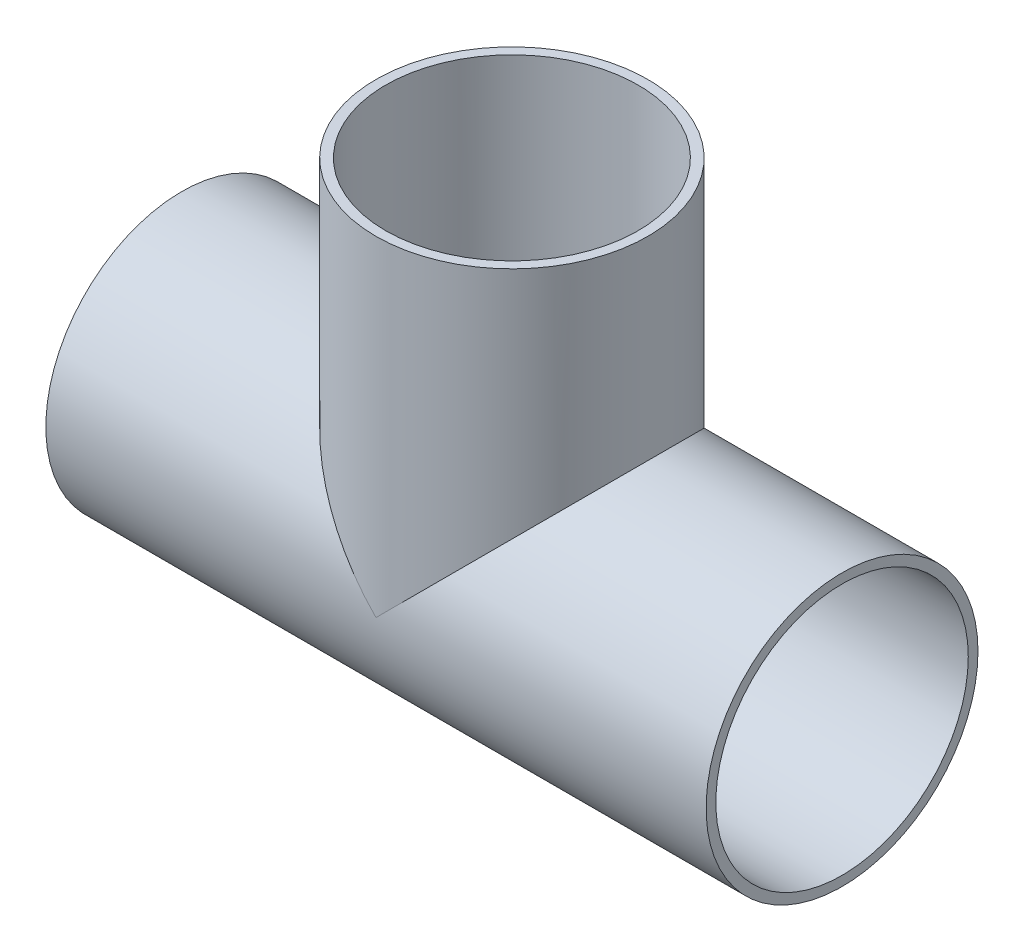
SolidWorks part; units mm, degrees
ref_plane "Front Plane" through (0, 0, 0) normal (0, 0, 1) x (1, 0, 0)
ref_plane "Top Plane" through (0, 0, 0) normal (0, 1, 0) x (1, 0, 0)
ref_plane "Right Plane" through (0, 0, 0) normal (1, 0, 0) x (0, 0, -1)
sketch "Sketch1" plane through (0, 0, 0) normal (1, 0, 0) x (0, 0, -1)
  circle A0 centre (0, 0) radius 32.5
  circle A1 centre (0, 0) radius 35
extrude "Boss-Extrude1" add sketch "Sketch1" along normal blind 170
sketch "Sketch2" plane through (0, 0, 0) normal (0, 1, 0) x (1, 0, 0)
  line L0 (85, 35) -> (85, -35) construction
  line L1 (170, 35) -> (0, 35) construction
  line L2 (0, -35) -> (170, -35) construction
  line L3 (0, 0) -> (170, 0) construction
  line L4 (170, -35) -> (170, 35) construction
  circle A0 centre (85, 0) radius 35
  circle A1 centre (85, 0) radius 32.5
extrude "Boss-Extrude2" add sketch "Sketch2" along normal blind 85
sketch "Sketch4" plane through (0, 0, 0) normal (1, 0, 0) x (0, 0, -1)
  line L0 (-32.5, 0) -> (32.5, 0) construction
  circle A0 centre (0, 0) radius 32.5
extrude "Cut-Extrude2" cut sketch "Sketch4" along normal blind 170
sketch "Sketch5" plane through (0, 0, 0) normal (0, 1, 0) x (1, 0, 0)
  circle A0 centre (85, 0) radius 32.5
extrude "Cut-Extrude4" cut sketch "Sketch5" along normal blind 85
